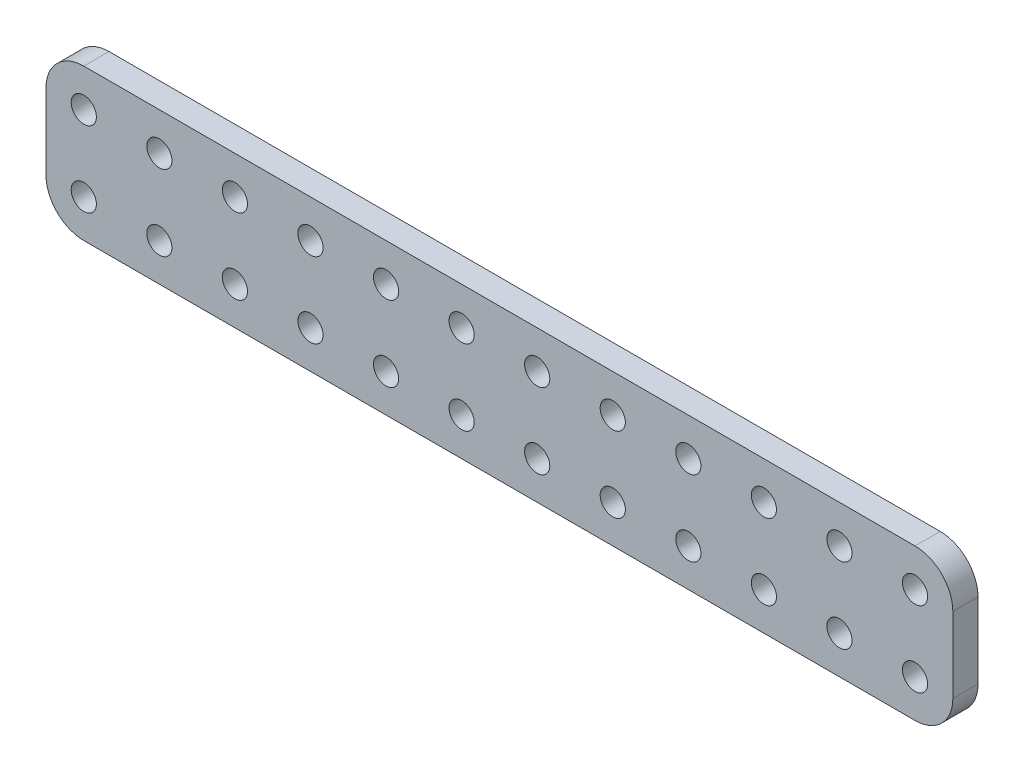
SolidWorks part; units mm, degrees
ref_plane "Alzado" through (0, 0, 0) normal (0, 0, 1) x (1, 0, 0)
ref_plane "Planta" through (0, 0, 0) normal (0, 1, 0) x (1, 0, 0)
ref_plane "Vista lateral" through (0, 0, 0) normal (1, 0, 0) x (0, 0, -1)
sketch "Model" plane through (0, 0, 0) normal (0, 0, 1) x (1, 0, 0)
  line L0 (256.4291, 228.7422) -> (355.4291, 228.7422)
  line L1 (355.4291, 210.7422) -> (256.4291, 210.7422)
  line L2 (359.9291, 224.2422) -> (359.9291, 215.2422)
  line L3 (251.9291, 224.2422) -> (251.9291, 215.2422)
  arc A0 (359.9291, 224.2422) -> (355.4291, 228.7422) centre (355.4291, 224.2422) ccw
  arc A1 (256.4291, 228.7422) -> (251.9291, 224.2422) centre (256.4291, 224.2422) ccw
  arc A2 (251.9291, 215.2422) -> (256.4291, 210.7422) centre (256.4291, 215.2422) ccw
  arc A3 (355.4291, 210.7422) -> (359.9291, 215.2422) centre (355.4291, 215.2422) ccw
  circle A4 centre (310.4291, 224.2422) radius 1.5
  circle A5 centre (292.4291, 224.2422) radius 1.5
  circle A6 centre (301.4291, 224.2422) radius 1.5
  circle A7 centre (337.4291, 215.2422) radius 1.5
  circle A8 centre (319.4291, 215.2422) radius 1.5
  circle A9 centre (328.4291, 215.2422) radius 1.5
  circle A10 centre (310.4291, 215.2422) radius 1.5
  circle A11 centre (292.4291, 215.2422) radius 1.5
  circle A12 centre (301.4291, 215.2422) radius 1.5
  circle A13 centre (274.4291, 215.2422) radius 1.5
  circle A14 centre (283.4291, 215.2422) radius 1.5
  circle A15 centre (265.4291, 215.2422) radius 1.5
  circle A16 centre (256.4291, 215.2422) radius 1.5
  circle A17 centre (346.4291, 215.2422) radius 1.5
  circle A18 centre (274.4291, 224.2422) radius 1.5
  circle A19 centre (265.4291, 224.2422) radius 1.5
  circle A20 centre (256.4291, 224.2422) radius 1.5
  circle A21 centre (283.4291, 224.2422) radius 1.5
  circle A22 centre (337.4291, 224.2422) radius 1.5
  circle A23 centre (319.4291, 224.2422) radius 1.5
  circle A24 centre (328.4291, 224.2422) radius 1.5
  circle A25 centre (346.4291, 224.2422) radius 1.5
  circle A26 centre (355.4291, 215.2422) radius 1.5
  circle A27 centre (355.4291, 224.2422) radius 1.5
extrude "Saliente-Extruir1" add sketch "Model" along normal blind 3
